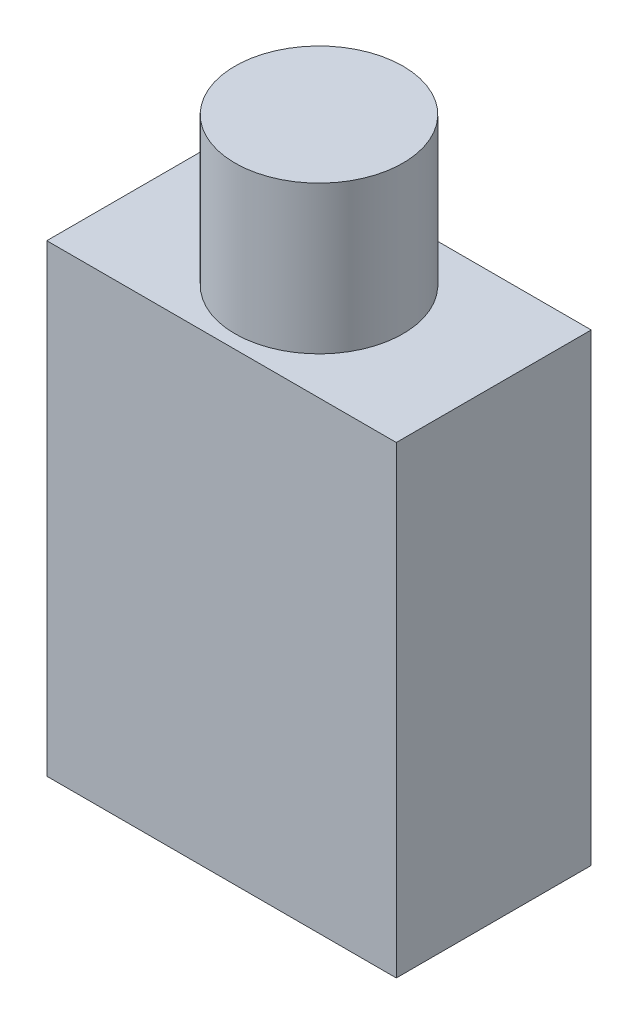
SolidWorks part; units mm, degrees
material "ABS"
ref_plane "Front Plane" through (0, 0, 0) normal (0, 0, 1) x (1, 0, 0)
ref_plane "Top Plane" through (0, 0, 0) normal (0, 1, 0) x (1, 0, 0)
ref_plane "Right Plane" through (0, 0, 0) normal (1, 0, 0) x (0, 0, -1)
sketch "Sketch1" plane through (0, 0, 0) normal (0, 0, 1) x (1, 0, 0)
  line L1 (0, 0) -> (52, 0)
  line L2 (0, 0) -> (0, -69)
  line L3 (0, -69) -> (52, -69)
  line L4 (52, 0) -> (52, -69)
  dimension "D1" = 69
  dimension "D2" = 52
extrude "Boss-Extrude1" add sketch "Sketch1" along normal blind 29
sketch "Sketch2" plane through (0, 0, 0) normal (0, 1, 0) x (1, 0, 0)
  line L0 (52, 0) -> (0, 0) construction
  line L1 (52, -29) -> (52, 0) construction
  circle A0 centre (26, -14.5) radius 12.5
  dimension "D1" = 25
  dimension "D2" = 14.5
  dimension "D3" = 26
extrude "Boss-Extrude2" add sketch "Sketch2" along normal blind 22
equation "\"D2@Sketch2\"=\"D1@Boss-Extrude1\"/2"
equation "\"D3@Sketch2\"=\"D2@Sketch1\"/2"
